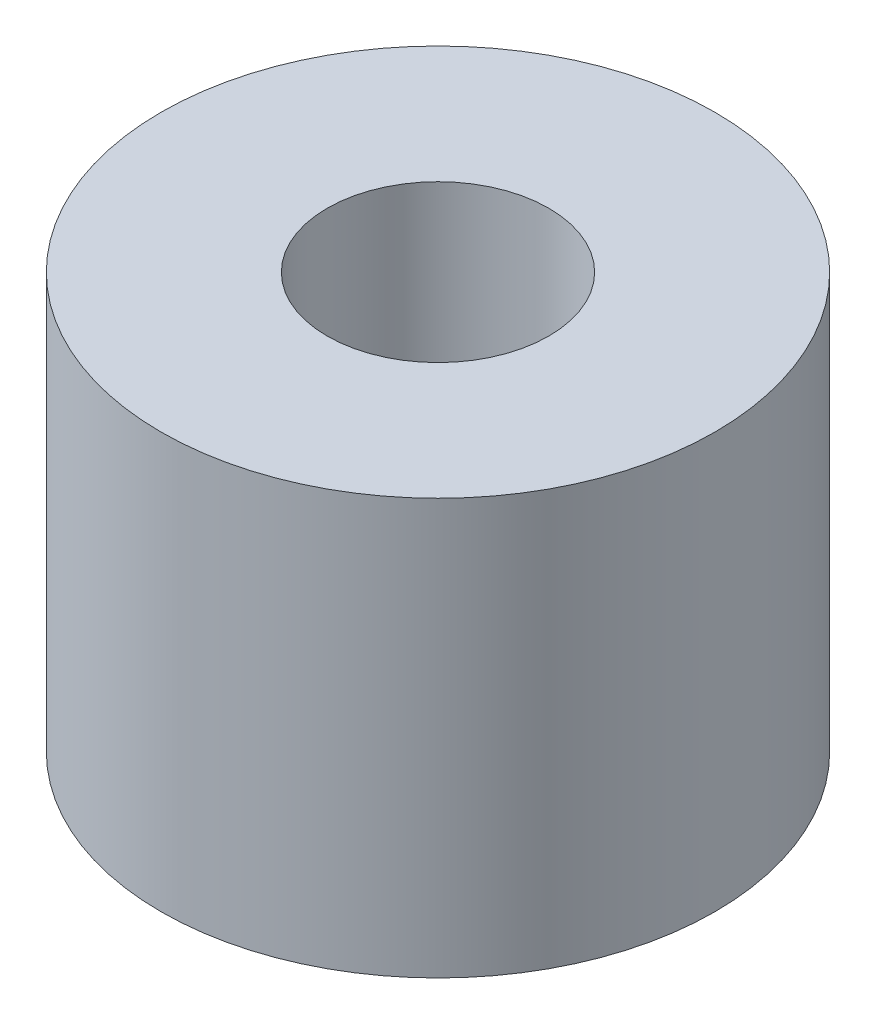
SolidWorks part; units mm, degrees
ref_plane "前视基准面" through (0, 0, 0) normal (0, 0, 1) x (1, 0, 0)
ref_plane "上视基准面" through (0, 0, 0) normal (0, 1, 0) x (1, 0, 0)
ref_plane "右视基准面" through (0, 0, 0) normal (1, 0, 0) x (0, 0, -1)
other "Configuration Table"
sketch "草图1" plane through (0, 0, 0) normal (0, 1, 0) x (1, 0, 0)
  circle A0 centre (0, 0) radius 10
extrude "凸台-拉伸1" add sketch "草图1" along normal blind 15
sketch "草图2" plane through (0, 0, 0) normal (0, 1, 0) x (1, 0, 0)
  circle A0 centre (0, 0) radius 4
extrude "切除-拉伸1" cut sketch "草图2" along normal blind 15
